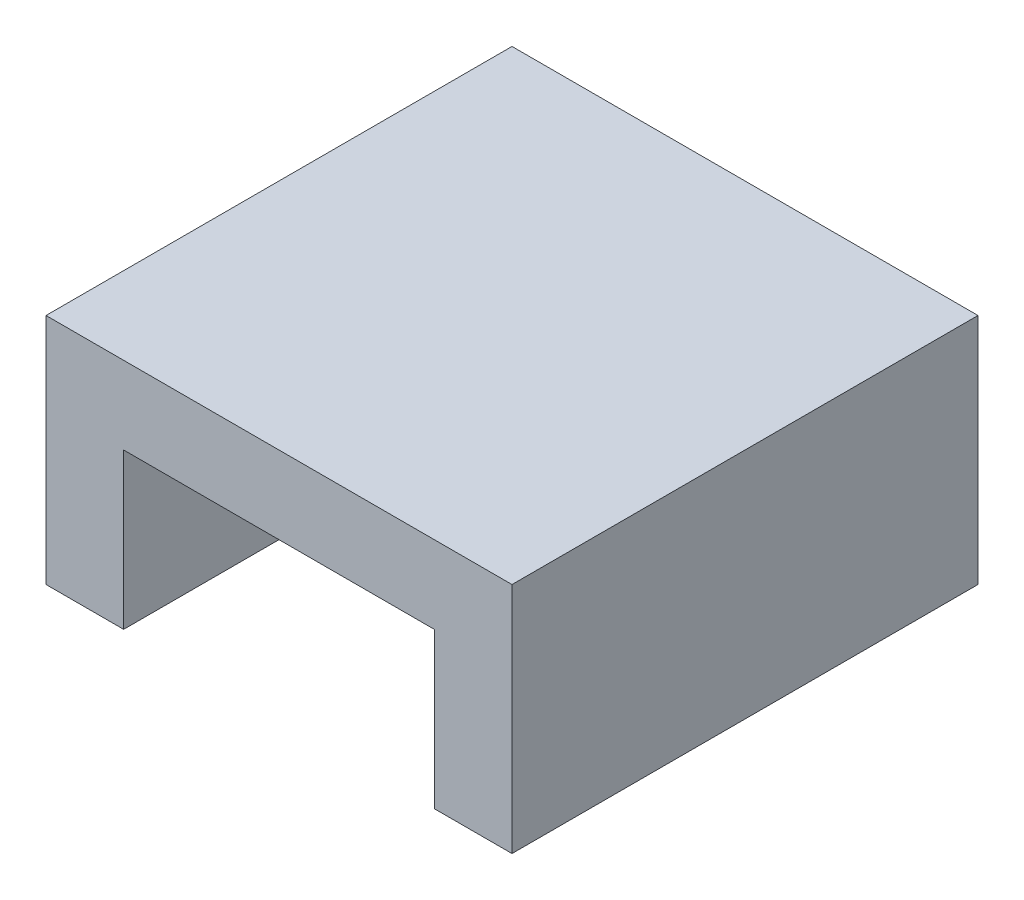
SolidWorks part; units mm, degrees
material "1060 Alloy"
ref_plane "Front Plane" through (0, 0, 0) normal (0, 0, 1) x (1, 0, 0)
ref_plane "Top Plane" through (0, 0, 0) normal (0, 1, 0) x (1, 0, 0)
ref_plane "Right Plane" through (0, 0, 0) normal (1, 0, 0) x (0, 0, -1)
sketch "Sketch1" plane through (0, 0, 0) normal (0, 0, 1) x (1, 0, 0)
  line L0 (-12.7, 0) -> (-12.7, 12.7)
  line L1 (-12.7, 12.7) -> (12.7, 12.7) construction
  line L2 (-12.7, 12.7) -> (-12.7, -12.7) construction
  line L3 (-12.7, -12.7) -> (12.7, -12.7) construction
  line L4 (12.7, 12.7) -> (12.7, -12.7) construction
  line L5 (-12.7, 12.7) -> (12.7, -12.7) construction
  line L6 (-12.7, -12.7) -> (12.7, 12.7) construction
  line L7 (-12.7, 12.7) -> (12.7, 12.7)
  line L8 (12.7, 12.7) -> (12.7, 0)
  line L9 (-19.05, 0) -> (-19.05, 19.05)
  line L10 (-19.05, 19.05) -> (19.05, 19.05)
  line L11 (19.05, 19.05) -> (19.05, 0)
  line L12 (-19.05, 0) -> (-12.7, 0)
  line L13 (12.7, 0) -> (19.05, 0)
  point P0 (0, 0)
  dimension "D1" = 25.4
  dimension "D2" = 6.35
extrude "Boss-Extrude1" add sketch "Sketch1" along normal blind 38.1
